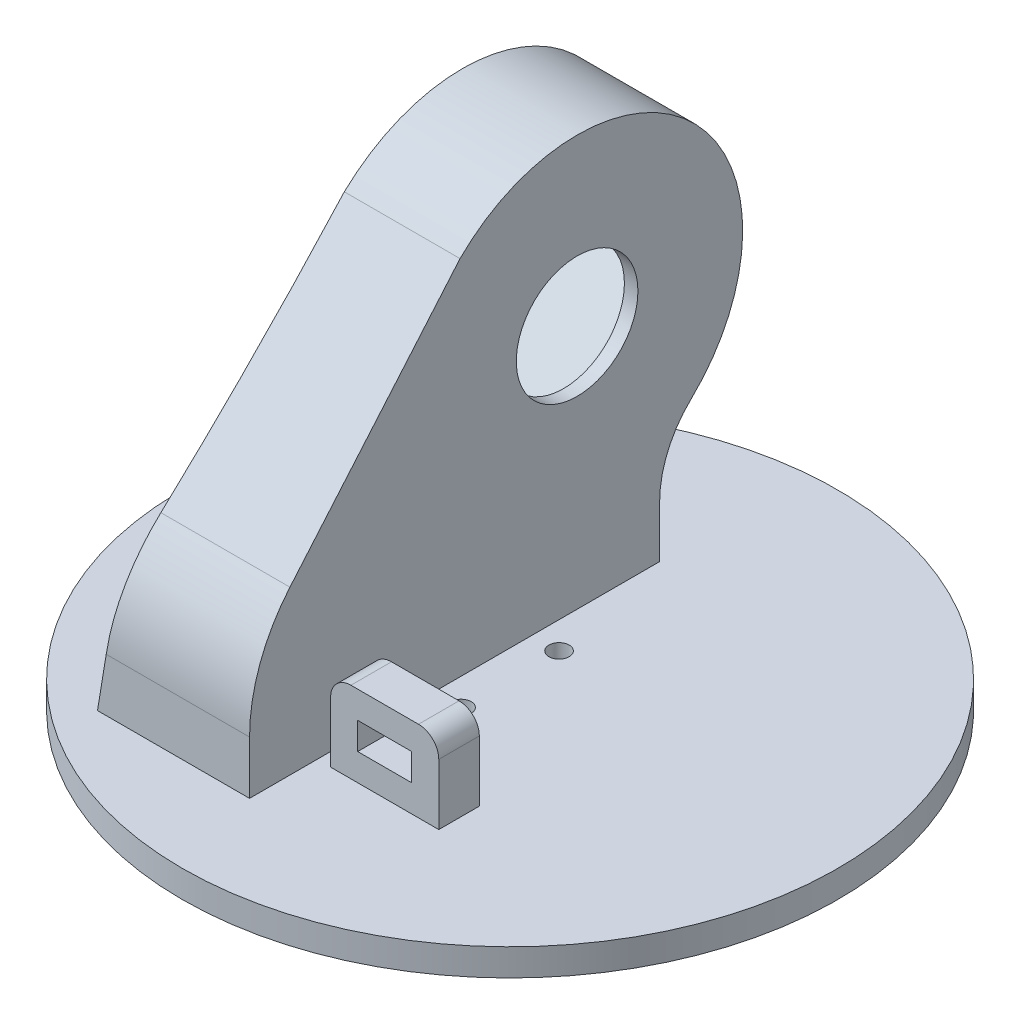
SolidWorks part; units mm, degrees
ref_plane "Front Plane" through (0, 0, 0) normal (0, 0, 1) x (1, 0, 0)
ref_plane "Top Plane" through (0, 0, 0) normal (0, 1, 0) x (1, 0, 0)
ref_plane "Right Plane" through (0, 0, 0) normal (1, 0, 0) x (0, 0, -1)
sketch "Sketch2" plane through (0, 0, 0) normal (0, 1, 0) x (1, 0, 0)
  circle A0 centre (0, 0) radius 48.5
  dimension "D1" = 97
extrude "Boss-Extrude1" add sketch "Sketch2" along normal blind 4
sketch "Sketch4" plane through (0, 0, 0) normal (0, -1, 0) x (1, 0, 0)
  circle A0 centre (0, 7.25) radius 1.5
  circle A1 centre (0, -7.25) radius 1.5
  dimension "D1" = 3
  dimension "D2" = 3
  dimension "D3" = 14.5
  dimension "D4" = 7.25
extrude "Cut-Extrude2" cut sketch "Sketch4" against normal through all
sketch "Sketch5" plane through (0, 0, 0) normal (0, -1, 0) x (1, 0, 0)
  circle A0 centre (0, 0) radius 3.75
  dimension "D1" = 7.5
extrude "Cut-Extrude3" cut sketch "Sketch5" against normal blind 1.5
ref_plane "Plane1" through (-4, 0, 0) normal (1, 0, 0) x (0, 0, -1)
sketch "Sketch7" plane through (-4, 0, 0) normal (1, 0, 0) x (0, 0, -1)
  line L0 (23.1299, 11.6445) -> (23.1299, 4)
  line L5 (48.5, 4) -> (-48.5, 4) construction
  line L6 (-27.2273, 29.5362) -> (-1.2843, 55.4793)
  line L7 (-43.5609, 4) -> (23.1299, 4)
  line L11 (-34.5496, 4) -> (-34.5496, 11.8586)
  arc A4 (28.7298, 24.692) -> (-1.2843, 55.4793) centre (13.9185, 40.2765) ccw
  arc A5 (28.7298, 24.692) -> (23.1299, 11.6445) centre (41.1299, 11.6445) ccw
  arc A6 (-27.2273, 29.5362) -> (-34.5496, 11.8586) centre (-9.5496, 11.8586) ccw
  dimension "D1" = 25
  dimension "D4" = 43
  dimension "D3" = 18
  dimension "D5" = 45
extrude "Boss-Extrude2" add sketch "Sketch7" against normal blind 14
ref_plane "Plane2" through (-6, 0, 0) normal (1, 0, 0) x (0, 0, -1)
sketch "Sketch8" plane through (-6, 0, 0) normal (1, 0, 0) x (0, 0, -1)
  line L0 (-27.2273, 29.5362) -> (-1.2843, 55.4793) construction
  line L1 (-15.2496, 25.9576) -> (13.7417, 54.9489)
  line L2 (-15.2496, 25.9576) -> (-0.4004, 11.1083)
  line L3 (-0.4004, 11.1083) -> (28.591, 40.0997)
  line L4 (13.7417, 54.9489) -> (28.591, 40.0997)
  line L5 (-15.2496, 25.9576) -> (28.591, 40.0997) construction
  line L6 (-0.4004, 11.1083) -> (13.7417, 54.9489) construction
  point P0 (6.6707, 33.0286)
  point P11 (13.9185, 40.2765)
  dimension "D1" = 41
  dimension "D2" = 21
  dimension "D3" = 90
  dimension "D4" = 20.5
  dimension "D5" = 90
  dimension "D6" = 10.25
  dimension "D7" = 10.5
extrude "Cut-Extrude5" cut sketch "Sketch8" against normal up to next
sketch "Sketch9" plane through (-18, 0, 0) normal (-1, 0, 0) x (0, 0, 1)
  line L0 (-13.7417, 54.9489) -> (-28.591, 40.0997) construction
  line L3 (-21.1664, 47.5243) -> (-22.536, 48.894) construction
  circle A0 centre (-20.1057, 53.5347) radius 1.3
  circle A1 centre (-27.1768, 46.4637) radius 1.3
  circle A2 centre (6.7644, 12.5225) radius 1.3
  circle A3 centre (13.8354, 19.5936) radius 1.3
  dimension "D1" = 2.6
  dimension "D5" = 5
  dimension "D6" = 90
  dimension "D2" = 3.5
  dimension "D3" = 2
  dimension "D4" = 2
extrude "Cut-Extrude6" cut sketch "Sketch9" against normal blind 7.5
sketch "Sketch11" plane through (-4, 0, 0) normal (1, 0, 0) x (0, 0, -1)
  circle A0 centre (13.9185, 40.2765) radius 9
  dimension "D1" = 18
extrude "Cut-Extrude9" cut sketch "Sketch11" against normal up to next
sketch "Sketch17" plane through (-18, 0, 0) normal (-1, 0, 0) x (0, 0, 1)
  line L0 (29.3486, 31.6576) -> (3.4056, 57.6006)
  line L1 (-26.1299, 11.6445) -> (-26.1299, 1)
  line L2 (-26.1299, 1) -> (37.5496, 1)
  line L3 (37.5496, 1) -> (37.5496, 11.8586)
  line L4 (27.2273, 29.5362) -> (1.2843, 55.4793)
  line L5 (-23.1299, 11.6445) -> (-23.1299, 4)
  line L6 (-23.1299, 4) -> (34.5496, 4)
  line L7 (34.5496, 4) -> (34.5496, 11.8586)
  line L9 (-23.1299, 11.6445) -> (-23.1299, 4)
  line L10 (-23.1299, 4) -> (34.5496, 4)
  line L11 (34.5496, 4) -> (34.5496, 11.8586)
  line L12 (-26.1299, 4) -> (37.5496, 4)
  line L13 (48.5, 4) -> (-48.5, 4) construction
  line L14 (3.4056, 57.6006) -> (28.5745, 28.0776)
  line L15 (1.2843, 55.4793) -> (26.295, 26.1272)
  line L16 (31.5496, 11.8586) -> (31.5496, 4)
  line L18 (27.2273, 29.5362) -> (1.2843, 55.4793) construction
  arc A0 (3.4056, 57.6006) -> (-30.7965, 22.5174) centre (-13.9185, 40.2765) ccw
  arc A1 (-26.1299, 11.6445) -> (-30.7965, 22.5174) centre (-41.1299, 11.6445) ccw
  arc A2 (37.5496, 11.8586) -> (29.3486, 31.6576) centre (9.5496, 11.8586) ccw
  arc A3 (1.2843, 55.4793) -> (-28.7298, 24.692) centre (-13.9185, 40.2765) ccw
  arc A4 (-23.1299, 11.6445) -> (-28.7298, 24.692) centre (-41.1299, 11.6445) ccw
  arc A5 (34.5496, 11.8586) -> (27.2273, 29.5362) centre (9.5496, 11.8586) ccw
  arc A6 (1.2843, 55.4793) -> (-28.7298, 24.692) centre (-13.9185, 40.2765) ccw
  arc A7 (-23.1299, 11.6445) -> (-28.7298, 24.692) centre (-41.1299, 11.6445) ccw
  arc A8 (34.5496, 11.8586) -> (27.2273, 29.5362) centre (9.5496, 11.8586) ccw
  arc A9 (31.5496, 11.8586) -> (25.106, 27.4149) centre (9.5496, 11.8586) ccw
  line M16 (27.2273, 29.5362) -> (1.2843, 55.4793)
  arc M17 (1.2843, 55.4793) -> (-28.7298, 24.692) centre (-13.9185, 40.2765) ccw
  arc M18 (-28.7298, 24.692) -> (-23.1299, 11.6445) centre (-41.1299, 11.6445) cw
  line M19 (-23.1299, 11.6445) -> (-23.1299, 4)
  line M21 (34.5496, 4) -> (34.5496, 11.8586)
  arc M22 (34.5496, 11.8586) -> (27.2273, 29.5362) centre (9.5496, 11.8586) ccw
  dimension "D1" = 0
  dimension "D2" = 3
  dimension "D3" = 3
extrude "Boss-Extrude7" add sketch "Sketch17" along normal blind 9 and the other way up to surface contours A9 L16 L12 L15 M21 M22 M16 | A1 L1 L12 L14 A0 M19 M18 M17 M16 M22 other way up to face at (-4, 40.2765, -22.9185)
sketch "Sketch25" plane through (-18, 0, 0) normal (-1, 0, 0) x (0, 0, 1)
  line L0 (-23.1299, 11.6445) -> (-23.1299, 4)
  line L1 (48.5, 4) -> (-48.5, 4) construction
  line L2 (-23.1299, 11.6445) -> (-23.1299, 4) construction
  line L3 (1.2843, 55.4793) -> (26.295, 26.1272) construction
  line L4 (31.5496, 4) -> (-23.1299, 4) construction
  line L5 (31.5496, 11.8586) -> (31.5496, 4) construction
  line L6 (31.5496, 4) -> (-23.1299, 4)
  line L7 (31.5496, 11.8586) -> (31.5496, 4)
  line L8 (1.2843, 55.4793) -> (26.295, 26.1272)
  arc A0 (-23.1299, 11.6445) -> (-28.7298, 24.692) centre (-41.1299, 11.6445) ccw construction
  arc A1 (1.2843, 55.4793) -> (-28.7298, 24.692) centre (-13.9185, 40.2765) ccw construction
  arc A2 (-23.1299, 11.6445) -> (-28.7298, 24.692) centre (-41.1299, 11.6445) ccw
  arc A3 (31.5496, 11.8586) -> (26.295, 26.1272) centre (9.5496, 11.8586) ccw construction
  arc A4 (31.5496, 11.8586) -> (26.295, 26.1272) centre (9.5496, 11.8586) ccw
  spline S0 degree 3 poles (-28.7298, 24.692) (-21.9549, 18.2532) (-19.0941, 12.798) (-15.1299, 4) knots 0 0 0 0 1 1 1 1
  spline S1 degree 2 poles (11.7516, 43.195) (26.5513, 25.8264) (25.5496, 4) knots 0 0 0 1 1 1
  dimension "D2" = 8
  dimension "D1" = 6
extrude "Boss-Extrude10" add sketch "Sketch25" along normal up to surface (9 mm away) contours S0 L6 L0 A2 | A4 S1 A2 S0 L8 up to face at (-27, 22.2911, 0.3951)
sketch "Sketch26" plane through (0, 0, 0) normal (0, 0, 1) x (1, 0, 0)
  line L0 (-4, 64.7765) -> (-27, 64.7765) construction
  line L1 (-27, 4) -> (-4, 4) construction
  line L2 (-27, 4) -> (-27, 11.8586) construction
  line L3 (-26, 64.7765) -> (-27, 64.7765)
  line L4 (-27, 64.7765) -> (-27, 4)
  line L5 (-27, 4) -> (-23, 4)
  spline S0 degree 2 poles (-26, 64.7765) (-24.7724, 34.3751) (-23, 4) knots 0 0 0 1 1 1
  dimension "D1" = 1
  dimension "D2" = 4
  dimension "D3" = 2
extrude "Cut-Extrude15" [suppressed] cut sketch "Sketch26" against normal through all both and the other way through all contours L4 L5 S0 L3
sketch "Sketch27" plane through (0, 4, 0) normal (0, 1, 0) x (1, 0, 0)
  line L1 (-2, -18.5496) -> (14, -18.5496)
  line L2 (-2, -18.5496) -> (-2, -24.5496)
  line L3 (-2, -24.5496) -> (14, -24.5496)
  line L4 (14, -18.5496) -> (14, -24.5496)
  line L5 (-27, -34.5496) -> (-4, -34.5496) construction
  line L6 (-4, -34.5496) -> (-4, 26.1299) construction
  dimension "D1" = 10
  dimension "D2" = 6
  dimension "D3" = 16
  dimension "D4" = 2
extrude "Boss-Extrude11" add sketch "Sketch27" along normal blind 12
fillet "Fillet6" radius 3 2 edges at (14, 16, 21.5496) (-2, 16, 21.5496)
sketch "Sketch28" plane through (0, 0, 24.5496) normal (0, 0, 1) x (1, 0, 0)
  line L8 (10, 12) -> (2, 12)
  line L9 (2, 12) -> (2, 8)
  line L10 (2, 8) -> (10, 8)
  line L11 (10, 8) -> (10, 12)
  line L12 (10, 12) -> (2, 12)
  line L13 (2, 12) -> (2, 8)
  line L14 (2, 8) -> (10, 8)
  line L15 (10, 8) -> (10, 12)
  dimension "D1" = 4
extrude "Cut-Extrude16" cut sketch "Sketch28" against normal up to next
sketch "Sketch29" plane through (0, 0, 0) normal (0, 0, 1) x (1, 0, 0)
  line L0 (-4, 64.7765) -> (-27, 64.7765) construction
  line L1 (-27, 4) -> (-4, 4) construction
  line L2 (-21, 64.7765) -> (-27, 64.7765)
  line L3 (-27, 64.7765) -> (-27, 4)
  line L4 (-27, 4) -> (-26.5, 4)
  line L5 (48.5, 4) -> (-48.5, 4) construction
  spline S0 degree 2 poles (-21, 64.7765) (-21.2205, 34.1409) (-26.5, 4) knots 0 0 0 1 1 1
  dimension "D1" = 6
  dimension "D2" = 4
  dimension "D3" = 0.5
  dimension "D4" = 25
extrude "Cut-Extrude17" cut sketch "Sketch29" against normal through all both and the other way through all
